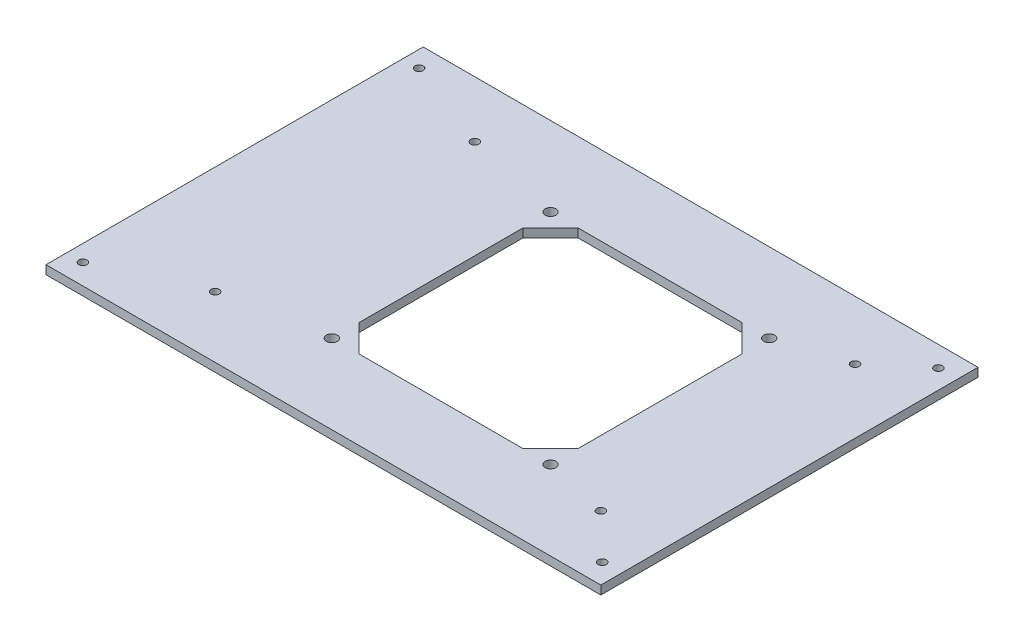
SolidWorks part; units mm, degrees
ref_plane "Front Plane" through (0, 0, 0) normal (0, 0, 1) x (1, 0, 0)
ref_plane "Top Plane" through (0, 0, 0) normal (0, 1, 0) x (1, 0, 0)
ref_plane "Right Plane" through (0, 0, 0) normal (1, 0, 0) x (0, 0, -1)
sketch "Sketch1" plane through (0, 0, 0) normal (0, 1, 0) x (1, 0, 0)
  line L1 (101.5, -69) -> (-101.5, -69)
  line L2 (101.5, -69) -> (101.5, 69)
  line L3 (101.5, 69) -> (-101.5, 69)
  line L4 (-101.5, -69) -> (-101.5, 69)
  line L5 (101.5, -69) -> (-101.5, 69) construction
  line L6 (101.5, 69) -> (-101.5, -69) construction
  point P0 (0, 0)
  dimension "D1" = 203
  dimension "D2" = 138
extrude "Boss-Extrude1" add sketch "Sketch1" along normal blind 3.175
sketch "Sketch4" plane through (0, 3.175, 0) normal (0, 1, 0) x (1, 0, 0)
  line L0 (101.5, 69) -> (-101.5, 69) construction
  line L2 (94.5, 61.5) -> (-95.5, 61.5) construction
  line L3 (94.5, 61.5) -> (94.5, -61.5) construction
  line L4 (94.5, -61.5) -> (-95.5, -61.5) construction
  line L5 (-95.5, 61.5) -> (-95.5, -61.5) construction
  line L6 (-101.5, 69) -> (-101.5, -69) construction
  point P0 (-62, 48.4)
  point P1 (78, 47.5)
  point P2 (78, -45.5)
  point P3 (-62, -46.6)
  point P5 (-95.5, -61.5)
  point P9 (94.5, 61.5)
  dimension "D1" = 140
  dimension "D2" = 93
  dimension "D3" = 95
  dimension "D4" = 140
  dimension "D5" = 0.9
  dimension "D6" = 14
  dimension "D7" = 7.5
  dimension "D8" = 123
  dimension "D9" = 190
  dimension "D10" = 6
  dimension "D11" = 16.5
hole_wizard "Ø3.0mm Dowel Hole1" positions "Sketch5" profile "Sketch6" hole size "Ø3.0" standard "ISO" end condition through all
sketch "Sketch5" plane through (0, 3.175, 0) normal (0, 1, 0) x (1, 0, 0)
  point P0 (-95.5, 61.5)
  point P3 (94.5, 61.5)
  point P6 (94.5, -61.5)
  point P9 (-95.5, -61.5)
  point P12 (-62, -46.6)
  point P15 (78, -45.5)
  point P18 (78, 47.5)
  point P21 (-62, 48.4)
sketch "Sketch6" plane through (-95.5, 3.175, -61.5) normal (1, 0, 0) x (0, 0, 1)
  line L0 (0, 0) -> (0, 3.175)
  line L1 (0, 3.175) -> (1.5, 3.175)
  line L2 (1.5, 3.175) -> (1.5, 0)
  line L5 (1.5, 0) -> (0, 0)
  line L11 (0, -6.35) -> (0, 107.95) construction
  dimension "Thru Hole Dia." = 3
  dimension "Thru Hole Depth" = 3.175
sketch "Sketch7" plane through (0, 3.175, 0) normal (0, 1, 0) x (1, 0, 0)
  line L0 (-25.9, 30) -> (-15.9, 40)
  line L1 (-25.9, 40) -> (54.1, 40) construction
  line L2 (-25.9, 40) -> (-25.9, -40) construction
  line L3 (-25.9, -40) -> (54.1, -40) construction
  line L4 (54.1, 40) -> (54.1, -40) construction
  line L5 (-15.9, 40) -> (44.1, 40)
  line L6 (-25.9, 30) -> (-25.9, -30)
  line L7 (-15.9, -40) -> (44.1, -40)
  line L8 (54.1, 30) -> (54.1, -30)
  line L9 (44.1, 40) -> (54.1, 30)
  line L10 (54.1, -30) -> (44.1, -40)
  line L11 (-25.9, -30) -> (-15.9, -40)
  line L12 (-25.9, 40) -> (54.1, -40) construction
  line L13 (54.1, 40) -> (-25.9, -40) construction
  point P4 (-25.9, 40)
  point P5 (54.1, -40)
  point P6 (-25.9, -40)
  point P7 (54.1, 40)
  point P16 (14.1, 0)
  dimension "D1" = 80
  dimension "D2" = 63.9
hole_wizard "Ø4.0mm Dowel Hole1" positions "Sketch8" profile "Sketch9" hole size "Ø4.0" standard "ISO" end condition through all
sketch "Sketch8" plane through (0, 3.175, 0) normal (0, 1, 0) x (1, 0, 0)
  point P0 (-25.9, 40)
  point P3 (54.1, 40)
  point P6 (54.1, -40)
  point P9 (-25.9, -40)
sketch "Sketch9" plane through (-25.9, 3.175, -40) normal (1, 0, 0) x (0, 0, 1)
  line L0 (0, 0) -> (0, 3.175)
  line L1 (0, 3.175) -> (2, 3.175)
  line L2 (2, 3.175) -> (2, 0)
  line L5 (2, 0) -> (0, 0)
  line L11 (0, -6.35) -> (0, 107.95) construction
  dimension "Thru Hole Dia." = 4
  dimension "Thru Hole Depth" = 3.175
extrude "Cut-Extrude1" cut sketch "Sketch7" against normal through all contours L0 L5 L9 L8 L10 L7 L11 L6
